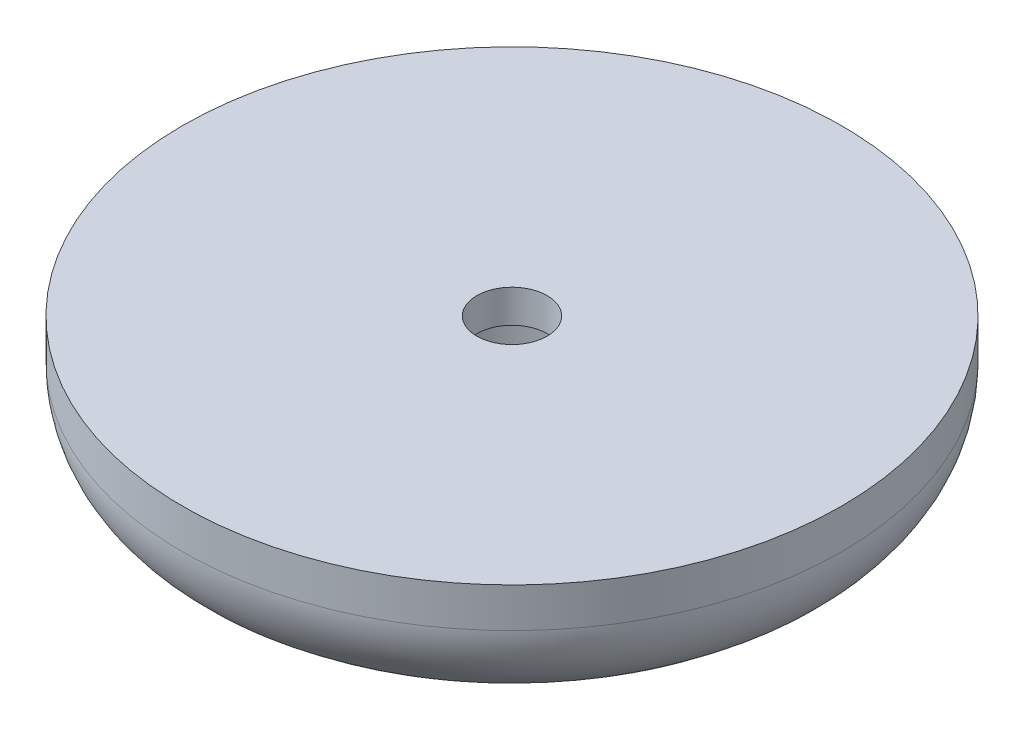
SolidWorks part; units mm, degrees
ref_plane "Front Plane" through (0, 0, 0) normal (0, 0, 1) x (1, 0, 0)
ref_plane "Top Plane" through (0, 0, 0) normal (0, 1, 0) x (1, 0, 0)
ref_plane "Right Plane" through (0, 0, 0) normal (1, 0, 0) x (0, 0, -1)
sketch "Sketch1" plane through (0, 0, 0) normal (0, 0, 1) x (1, 0, 0)
  line L1 (0, 0) -> (15, 0)
  line L2 (0, 0) -> (0, -5.8)
  line L3 (0, -5.8) -> (15, -5.8)
  line L4 (15, 0) -> (15, -5.8)
  dimension "D1" = 5.8
  dimension "D2" = 15
revolve "Revolve1" add sketch "Sketch1" angle 360 about L2
hole_wizard "CBORE for M3 SHCS1" positions "Sketch3" profile "Sketch4" counterbore size "M3" standard "ANSI Metric" end condition through all
sketch "Sketch3" plane through (0, -5.8, 0) normal (0, -1, 0) x (-1, 0, 0)
  point P0 (0, 0)
sketch "Sketch4" plane through (0, -5.8, 0) normal (1, 0, 0) x (0, 0, -1)
  line L0 (0, 0) -> (0, 5.8)
  line L1 (0, 5.8) -> (1.6, 5.8)
  line L3 (1.6, 5.8) -> (1.6, 4.3)
  line L4 (1.6, 4.3) -> (4, 4.3)
  line L5 (4, 4.3) -> (4, 0)
  line L7 (4, 0) -> (0, 0)
  line L11 (0, -6.35) -> (0, 107.95) construction
  dimension "Thru Hole Dia." = 3.2
  dimension "Thru Hole Depth" = 5.8
  dimension "C'Bore Dia." = 8
  dimension "C'Bore Depth" = 4.3
fillet "Fillet2" radius 4 1 edges at (-15, -5.8, 0)
fillet "Fillet3" radius 1 1 edges at (0, -5.8, -4)
